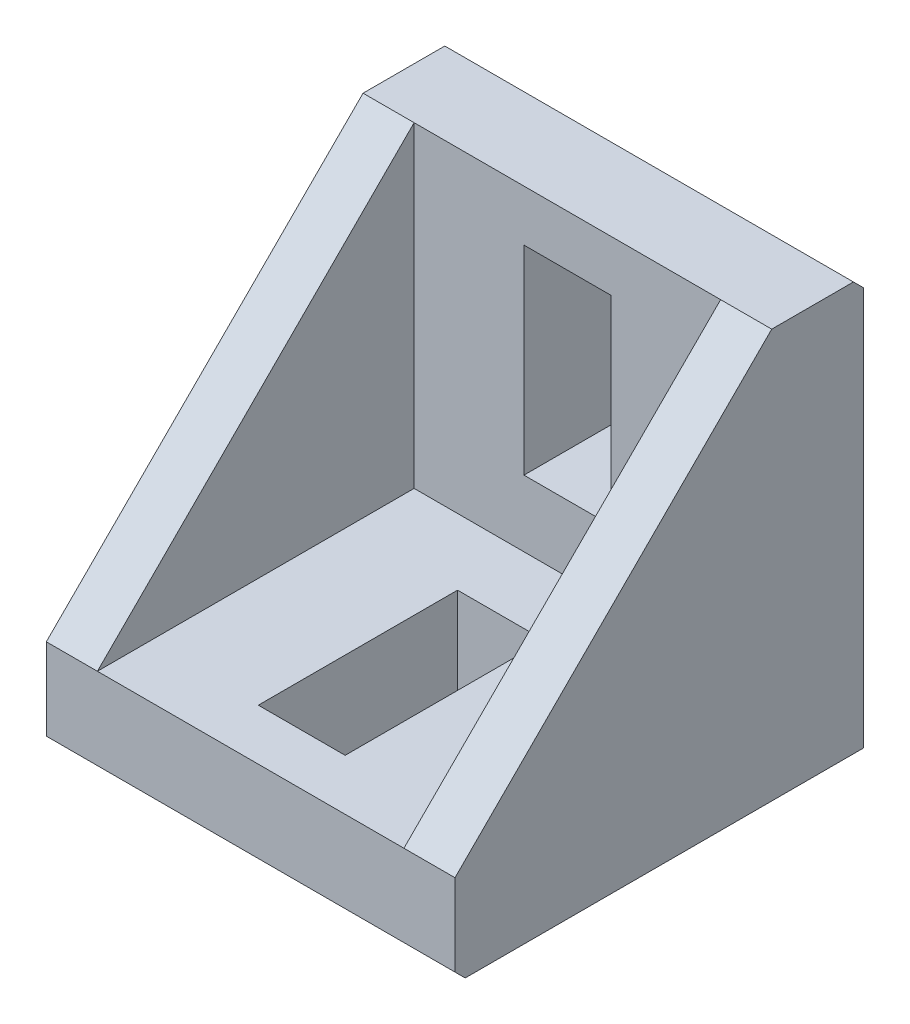
SolidWorks part; units mm, degrees
ref_plane "Front Plane" through (0, 0, 0) normal (0, 0, 1) x (1, 0, 0)
ref_plane "Top Plane" through (0, 0, 0) normal (0, 1, 0) x (1, 0, 0)
ref_plane "Right Plane" through (0, 0, 0) normal (1, 0, 0) x (0, 0, -1)
sketch "Sketch1" plane through (0, 0, 0) normal (0, 1, 0) x (1, 0, 0)
  line L1 (-20, 20) -> (20, 20)
  line L2 (-20, 20) -> (-20, -20)
  line L3 (-20, -20) -> (20, -20)
  line L4 (20, 20) -> (20, -20)
  line L5 (-20, 20) -> (20, -20) construction
  line L6 (-20, -20) -> (20, 20) construction
  point P0 (0, 0)
  dimension "D1" = 40
  dimension "D2" = 40
extrude "Boss-Extrude1" add sketch "Sketch1" along normal blind 9
sketch "Sketch2" plane through (0, 9, 0) normal (0, 1, 0) x (1, 0, 0)
  line L0 (20, -20) -> (20, 20) construction
  line L1 (-20, 20) -> (20, 20)
  line L2 (-20, 20) -> (-20, 11)
  line L3 (-20, 11) -> (20, 11)
  line L4 (20, 20) -> (20, 11)
  dimension "D1" = 9
extrude "Boss-Extrude2" add sketch "Sketch2" along normal blind 31
sketch "Sketch3" plane through (0, 9, 0) normal (0, 1, 0) x (1, 0, 0)
  line L0 (20, 20) -> (-20, 20) construction
  line L1 (-4.25, 4.5) -> (4.25, 4.5)
  line L2 (-4.25, 4.5) -> (-4.25, -15)
  line L3 (-4.25, -15) -> (4.25, -15)
  line L4 (4.25, 4.5) -> (4.25, -15)
  line L5 (-4.25, 4.5) -> (4.25, -15) construction
  line L6 (-4.25, -15) -> (4.25, 4.5) construction
  point P0 (0, -5.25)
  point P7 (0, 0)
  dimension "D1" = 15.5
  dimension "D2" = 19.5
  dimension "D3" = 8.5
extrude "Cut-Extrude1" cut sketch "Sketch3" against normal through all
sketch "Sketch4" plane through (0, 0, -11) normal (0, 0, 1) x (1, 0, 0)
  line L0 (-20, 0) -> (20, 0) construction
  line L1 (-4.25, 15.5) -> (4.25, 15.5)
  line L2 (-4.25, 15.5) -> (-4.25, 35)
  line L3 (-4.25, 35) -> (4.25, 35)
  line L4 (4.25, 15.5) -> (4.25, 35)
  line L5 (-4.25, 15.5) -> (4.25, 35) construction
  line L6 (-4.25, 35) -> (4.25, 15.5) construction
  point P0 (0, 25.25)
  point P7 (0, 0)
  dimension "D1" = 8.5
  dimension "D2" = 15.5
  dimension "D3" = 19.5
extrude "Cut-Extrude2" cut sketch "Sketch4" against normal through all
sketch "Sketch5" plane through (-20, 0, 0) normal (-1, 0, 0) x (0, 0, 1)
  line L0 (-11, 40) -> (20, 9)
  line L1 (20, 9) -> (-11, 9)
  line L2 (-11, 9) -> (-11, 40)
extrude "Boss-Extrude3" add sketch "Sketch5" against normal blind 5
sketch "Sketch6" plane through (20, 0, 0) normal (1, 0, 0) x (0, 0, -1)
  line L0 (-20, 9) -> (11, 40)
  line L1 (11, 40) -> (11, 9)
  line L2 (11, 9) -> (-20, 9)
extrude "Boss-Extrude4" add sketch "Sketch6" against normal blind 5
chamfer "Chamfer1" distance 1 angle 45 2 edges at (0, 0, 20) (0, 40, -20)
